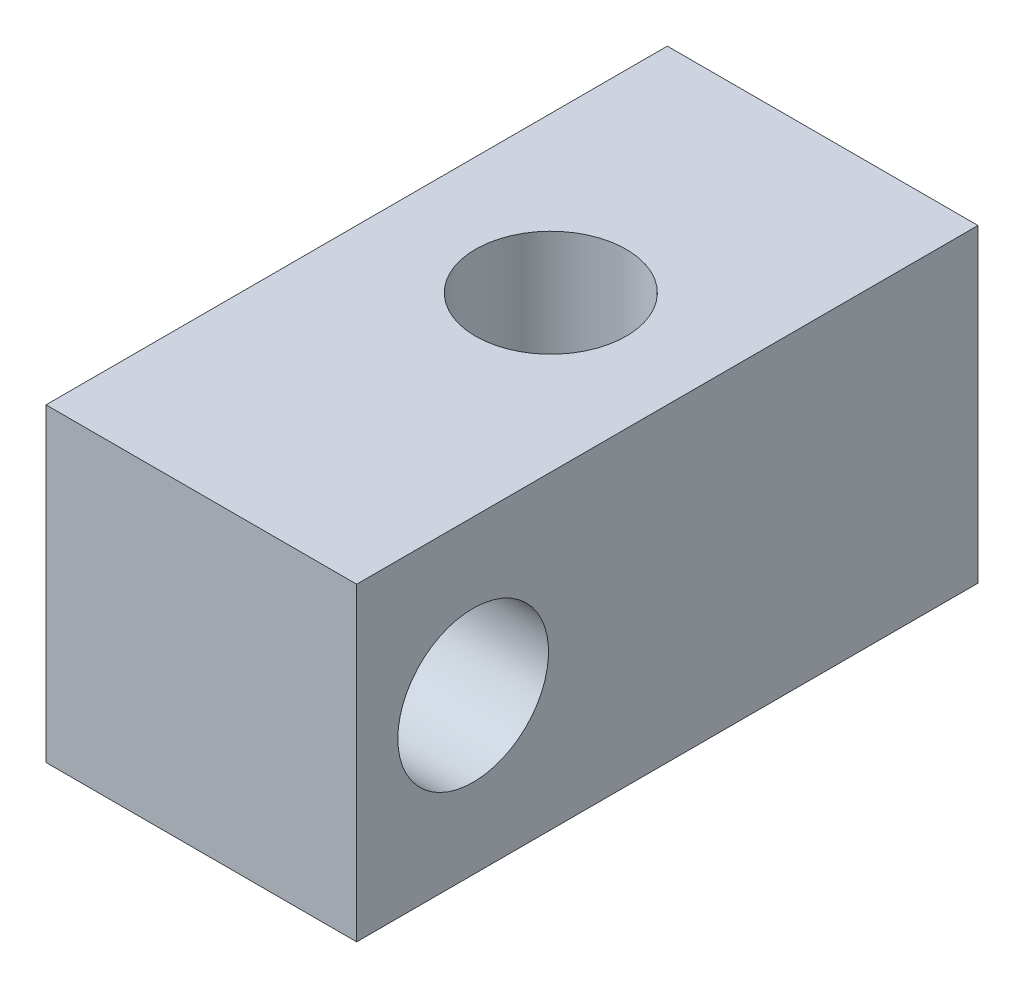
SolidWorks part; units mm, degrees
ref_plane "Front Plane" through (0, 0, 0) normal (0, 0, 1) x (1, 0, 0)
ref_plane "Top Plane" through (0, 0, 0) normal (0, 1, 0) x (1, 0, 0)
ref_plane "Right Plane" through (0, 0, 0) normal (1, 0, 0) x (0, 0, -1)
sketch "Sketch1" plane through (0, 0, 0) normal (0, 0, 1) x (1, 0, 0)
  line L1 (0, 0) -> (-10, 0)
  line L2 (0, 0) -> (0, 9.9709)
  line L3 (0, 9.9709) -> (-10, 9.9709)
  line L4 (-10, 0) -> (-10, 9.9709)
  line L5 (0, 0) -> (-10, 9.9709) construction
  line L6 (0, 9.9709) -> (-10, 0) construction
  point P4 (-5, 4.9855)
  dimension "D1" = 10
  dimension "10." = 9.9709
extrude "Boss-Extrude1" add sketch "Sketch1" along normal blind 20
sketch "Sketch26" plane through (0, 0, 0) normal (0, 0, -1) x (-1, 0, 0)
  line L0 (0, 9.9709) -> (10, 0) construction
  line L1 (0, 0) -> (10, 9.9709) construction
sketch "Sketch29" plane through (0, 0, 0) normal (0, 0, -1) x (-1, 0, 0)
  line L0 (0, 9.9709) -> (10, 0) construction
  point P0 (5, 4.9855)
hole_wizard "#11 (0.191) Diameter Hole6" positions "Sketch29" profile "Sketch28" hole size "#11" standard "ANSI Inch"
sketch "Sketch28" plane through (-5, 4.9855, 0) normal (1, 0, 0) x (0, 1, 0)
  line L0 (0, 0) -> (0, 5.4575)
  line L1 (0, 5.4575) -> (2.4257, 4)
  line L2 (2.4257, 4) -> (2.4257, 0)
  line L5 (2.4257, 0) -> (0, 0)
  line L10 (0, 5.4575) -> (-2.4257, 4) construction
  line L11 (0, -6.35) -> (0, 107.95) construction
  dimension "Hole Dia." = 4.8514
  dimension "Hole Depth" = 4
  dimension "Drill Angle" = 118
sketch "Sketch30" plane through (0, 9.9709, 0) normal (0, 1, 0) x (1, 0, 0)
  line L0 (0, -20) -> (0, 0) construction
  line L1 (-10, 0) -> (0, 0) construction
  line L2 (-10, 0) -> (-10, -6) construction
  line L3 (-10, -6) -> (0, -6) construction
  line L4 (0, 0) -> (0, -6) construction
  line L5 (-10, 0) -> (0, -6) construction
  line L6 (-10, -6) -> (0, 0) construction
  line L8 (-10, -6) -> (-5, -6) construction
  line L9 (-10, -6) -> (-10, -8.75) construction
  line L10 (-10, -8.75) -> (-5, -8.75) construction
  line L11 (-5, -6) -> (-5, -8.75) construction
  line L12 (-10, -6) -> (-5, -8.75) construction
  line L13 (-10, -8.75) -> (-5, -6) construction
  line L14 (-10, -8.75) -> (-5, -8.75) construction
  line L15 (-10, -8.75) -> (-10, -11.5) construction
  line L16 (-10, -11.5) -> (-5, -11.5) construction
  line L17 (-5, -8.75) -> (-5, -11.5) construction
  line L18 (-10, -8.75) -> (-5, -11.5) construction
  line L19 (-10, -11.5) -> (-5, -8.75) construction
  point P4 (-5, -3)
  point P11 (-7.5, -7.375)
  point P14 (-7.5, -10.125)
  dimension "D1" = 6
  dimension "D2" = 2.75
  dimension "D3" = 2.75
sketch "Sketch33" plane through (0, 9.9709, 0) normal (0, 1, 0) x (1, 0, 0)
  point P0 (-5, -8.75)
hole_wizard "#11 (0.191) Diameter Hole7" positions "Sketch33" profile "Sketch32" hole size "#11" standard "ANSI Inch" end condition through all
sketch "Sketch32" plane through (-5, 9.9709, 8.75) normal (1, 0, 0) x (0, 0, 1)
  line L0 (0, 0) -> (0, 9.9709)
  line L1 (0, 9.9709) -> (2.4257, 9.9709)
  line L2 (2.4257, 9.9709) -> (2.4257, 0)
  line L5 (2.4257, 0) -> (0, 0)
  line L11 (0, -6.35) -> (0, 107.95) construction
  dimension "Thru Hole Dia." = 4.8514
  dimension "Thru Hole Depth" = 9.9709
sketch "Sketch35" plane through (-10, 0, 0) normal (-1, 0, 0) x (0, 0, 1)
  line L0 (20, 9.9709) -> (0, 9.9709) construction
  line L1 (0, 0) -> (13.5, 0) construction
  line L2 (0, 0) -> (0, 9.9709) construction
  line L3 (0, 9.9709) -> (13.5, 9.9709) construction
  line L4 (13.5, 0) -> (13.5, 9.9709) construction
  line L5 (0, 0) -> (13.5, 9.9709) construction
  line L6 (0, 9.9709) -> (13.5, 0) construction
  line L8 (13.5, 0) -> (16.25, 0) construction
  line L9 (13.5, 0) -> (13.5, 5) construction
  line L10 (13.5, 5) -> (16.25, 5) construction
  line L11 (16.25, 0) -> (16.25, 5) construction
  line L12 (13.5, 0) -> (16.25, 5) construction
  line L13 (13.5, 5) -> (16.25, 0) construction
  line L14 (16.25, 0) -> (19, 0) construction
  line L15 (16.25, 0) -> (16.25, 5) construction
  line L16 (16.25, 5) -> (19, 5) construction
  line L17 (19, 0) -> (19, 5) construction
  line L18 (16.25, 0) -> (19, 5) construction
  line L19 (16.25, 5) -> (19, 0) construction
  point P4 (6.75, 4.9855)
  point P11 (14.875, 2.5)
  point P14 (17.625, 2.5)
  dimension "D1" = 13.5
  dimension "D2" = 2.75
  dimension "D3" = 5
  dimension "D4" = 2.75
sketch "Sketch38" plane through (-10, 0, 0) normal (-1, 0, 0) x (0, 0, 1)
  point P0 (16.25, 5)
hole_wizard "#11 (0.191) Diameter Hole8" positions "Sketch38" profile "Sketch37" hole size "#11" standard "ANSI Inch" end condition through all
sketch "Sketch37" plane through (-10, 5, 16.25) normal (0, 1, 0) x (0, 0, 1)
  line L0 (0, 0) -> (0, 10)
  line L1 (0, 10) -> (2.4257, 10)
  line L2 (2.4257, 10) -> (2.4257, 0)
  line L5 (2.4257, 0) -> (0, 0)
  line L11 (0, -6.35) -> (0, 107.95) construction
  dimension "Thru Hole Dia." = 4.8514
  dimension "Thru Hole Depth" = 10
